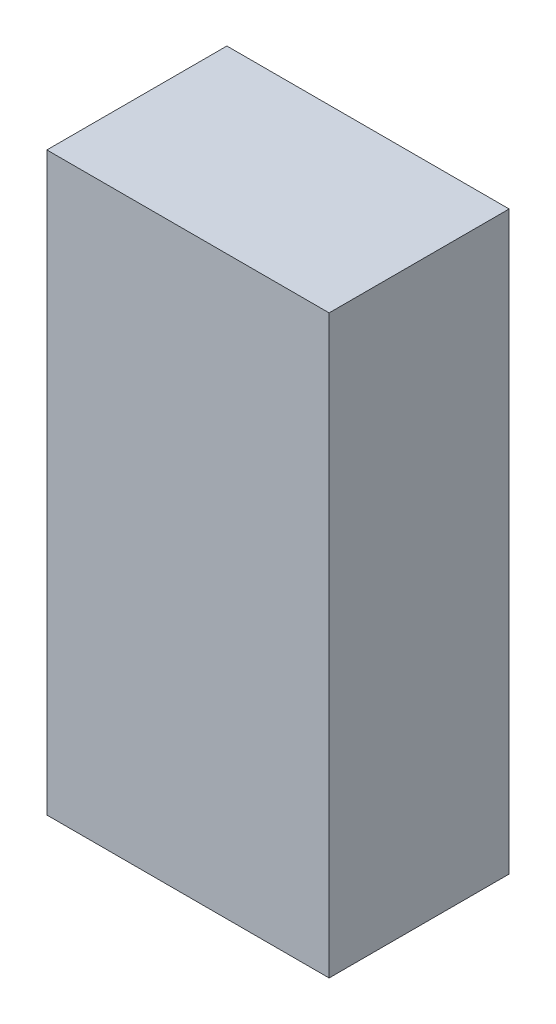
SolidWorks part; units mm, degrees
material "Balsa"
ref_plane "Front Plane" through (0, 0, 0) normal (0, 0, 1) x (1, 0, 0)
ref_plane "Top Plane" through (0, 0, 0) normal (0, 1, 0) x (1, 0, 0)
ref_plane "Right Plane" through (0, 0, 0) normal (1, 0, 0) x (0, 0, -1)
sketch "Sketch3" plane through (0, 0, 0) normal (0, 0, 1) x (1, 0, 0)
  line L1 (-6.223, 12.7) -> (6.223, 12.7)
  line L2 (-6.223, 12.7) -> (-6.223, -12.7)
  line L3 (-6.223, -12.7) -> (6.223, -12.7)
  line L4 (6.223, 12.7) -> (6.223, -12.7)
  line L5 (-6.223, 12.7) -> (6.223, -12.7) construction
  line L6 (-6.223, -12.7) -> (6.223, 12.7) construction
  point P0 (0, 0)
  dimension "D1" = 25.4
  dimension "D2" = 12.446
extrude "Boss-Extrude1" add sketch "Sketch3" along normal blind 7.9375
